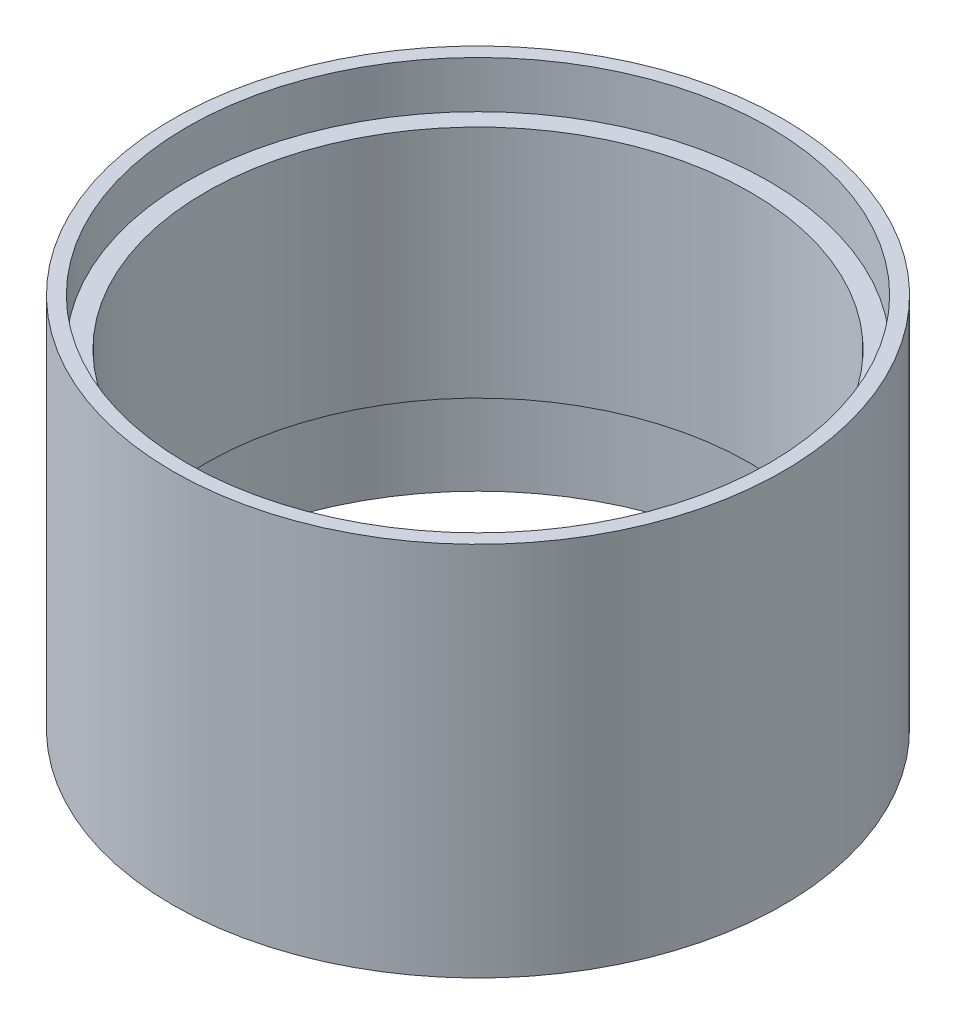
SolidWorks part; units mm, degrees
material "HYPALON"
ref_plane "Front Plane" through (0, 0, 0) normal (0, 0, 1) x (1, 0, 0)
ref_plane "Top Plane" through (0, 0, 0) normal (0, 1, 0) x (1, 0, 0)
ref_plane "Right Plane" through (0, 0, 0) normal (1, 0, 0) x (0, 0, -1)
sketch "Szkic1" plane through (0, 0, 0) normal (0, 0, 1) x (1, 0, 0)
  line L0 (0, 0) -> (-65, 0)
  line L1 (-65, 0) -> (-65, 20)
  line L2 (-62, 20) -> (-58, 20)
  line L3 (-58, 20) -> (-58, 70)
  line L4 (-62, 20) -> (-62, 0)
  line L5 (-58, 70) -> (-62, 70)
  line L6 (-65, 80) -> (-62, 80)
  line L7 (-65, 20) -> (-65, 80)
  line L8 (-62, 80) -> (-62, 70)
  line L13 (0, 0) -> (0, 22.4148)
  dimension "D1" = 65
  dimension "D2" = 20
  dimension "D3" = 7
  dimension "D4" = 3
  dimension "D5" = 3
  dimension "D6" = 10
  dimension "D7" = 80
revolve "Obrót1" add sketch "Szkic1" angle 360 about L13
